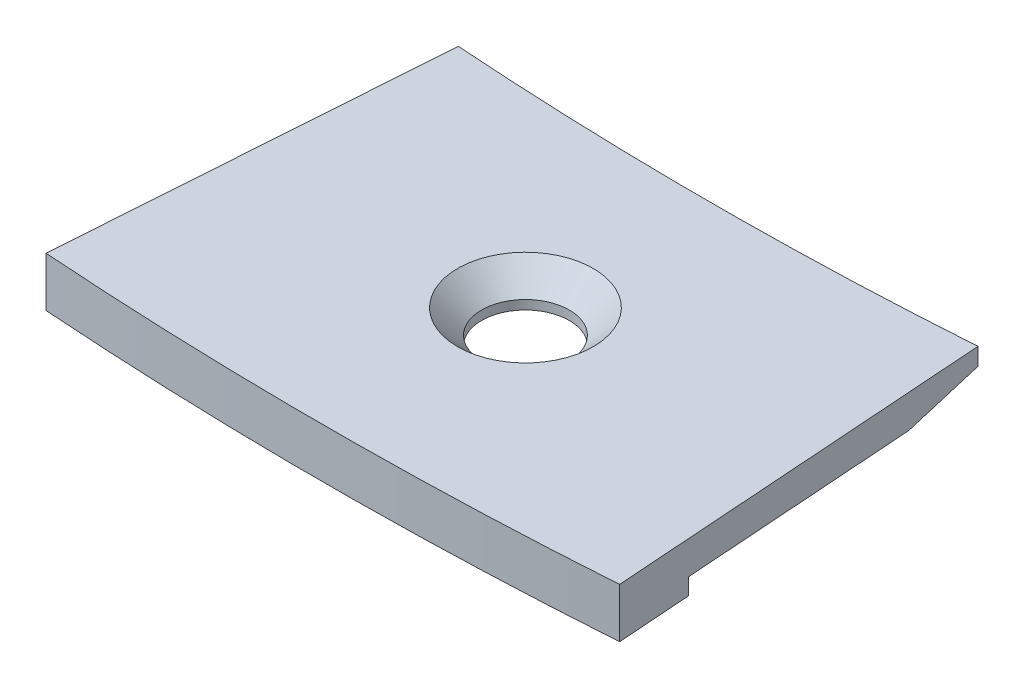
SolidWorks part; units mm, degrees
ref_plane "Front Plane" through (0, 0, 0) normal (0, 0, 1) x (1, 0, 0)
ref_plane "Top Plane" through (0, 0, 0) normal (0, 1, 0) x (1, 0, 0)
ref_plane "Right Plane" through (0, 0, 0) normal (1, 0, 0) x (0, 0, -1)
sketch "BASE" plane through (0, 0, 0) normal (0, 1, 0) x (1, 0, 0)
  line L0 (0, 0) -> (0, -243.5) construction
  line L1 (15.9742, -228.4422) -> (16.9857, -242.9068)
  line L2 (-15.9742, -228.4422) -> (-16.9857, -242.9068)
  line L3 (0, 0) -> (15.9742, -228.4422) construction
  line L4 (0, 0) -> (-15.9742, -228.4422) construction
  line L5 (0, -229) -> (0, -243.5) construction
  line L7 (-10, -226.25) -> (10, -226.25) construction
  line L8 (-10, -226.25) -> (-10, -246.25) construction
  line L9 (-10, -246.25) -> (10, -246.25) construction
  line L10 (10, -226.25) -> (10, -246.25) construction
  line L11 (-10, -226.25) -> (10, -246.25) construction
  line L12 (-10, -246.25) -> (10, -226.25) construction
  arc A0 (-16.9857, -242.9068) -> (16.9857, -242.9068) centre (0, 0) ccw
  arc A1 (-15.9742, -228.4422) -> (15.9742, -228.4422) centre (0, 0) ccw
  circle A2 centre (0, -236.25) radius 2.65
  dimension "D1" = 487
  dimension "D2" = 14.5
  dimension "D6" = 5.3
  dimension "D3" = 4
  dimension "D4" = 4
  dimension "D5" = 20
sketch "Sketch2" plane through (0, 0, 0) normal (0, 1, 0) x (1, 0, 0)
  line L1 (-15.9742, -228.4422) -> (-16.9857, -242.9068) construction
  line L3 (15.9742, -228.4422) -> (16.9857, -242.9068) construction
  line L4 (0, 0) -> (-17.3345, -247.8947) construction
  line L5 (0, 0) -> (17.3345, -247.8947) construction
  line L6 (-15.9847, -228.5918) -> (-17.3345, -247.8947)
  line L7 (15.9847, -228.5918) -> (17.3345, -247.8947)
  arc A0 (15.9847, -228.5918) -> (-15.9847, -228.5918) centre (0, 0) cw
  arc A1 (-15.9742, -228.4422) -> (15.9742, -228.4422) centre (0, 0) ccw construction
  arc A2 (17.3345, -247.8947) -> (-17.3345, -247.8947) centre (0, 0) cw
  arc A3 (-16.9857, -242.9068) -> (16.9857, -242.9068) centre (0, 0) ccw construction
  circle A4 centre (0, -236.25) radius 2.65
  dimension "D1" = 0.15
  dimension "D2" = 5
  dimension "D3" = 5.3
extrude "Boss-Extrude1" add sketch "Sketch2" along normal blind 2
sketch "Sketch3" plane through (0, 0, 0) normal (0, 1, 0) x (1, 0, 0)
  line L0 (0, 0) -> (15.9742, -228.4422) construction
  line L1 (0, 0) -> (-15.9742, -228.4422) construction
  line L2 (-15.7057, -224.6015) -> (-15.9847, -228.5918)
  line L3 (15.7057, -224.6015) -> (15.9847, -228.5918)
  arc A0 (15.9847, -228.5918) -> (-15.9847, -228.5918) centre (0, 0) cw
  arc A1 (15.7057, -224.6015) -> (-15.7057, -224.6015) centre (0, 0) cw
  dimension "D1" = 4
extrude "Boss-Extrude2" add sketch "Sketch3" against normal blind 2 from surface at 2 starting at face at (0, 2, 238.5341)
chamfer "Chamfer1" distance 4.5 angle 12 1 edges at (0, 0, 225.15)
sketch "Sketch4" plane through (0, 0, 0) normal (0, -1, 0) x (1, 0, 0)
  line L0 (15.9742, 228.4422) -> (16.9857, 242.9068) construction
  line L1 (-16.0196, 229.0906) -> (-17.3345, 247.8947) construction
  line L2 (17.3345, 247.8947) -> (16.0196, 229.0906) construction
  line L3 (-17.3345, 247.8947) -> (-17.0206, 243.4056)
  line L4 (17.3345, 247.8947) -> (17.0206, 243.4056)
  arc A0 (-17.0206, 243.4056) -> (17.0206, 243.4056) centre (0, 0) cw
  arc A1 (-17.3345, 247.8947) -> (17.3345, 247.8947) centre (0, 0) cw
  arc A2 (16.9857, 242.9068) -> (-16.9857, 242.9068) centre (0, 0) ccw construction
  arc A3 (17.3345, 247.8947) -> (-17.3345, 247.8947) centre (0, 0) ccw construction
  point P13 (0, 0)
  dimension "D2" = 0.5
extrude "Boss-Extrude3" add sketch "Sketch4" along normal blind 1
sketch "Sketch18" plane through (0, 2, 0) normal (0, 1, 0) x (1, 0, 0)
  circle A0 centre (0, -236.25) radius 4.225
  dimension "D1" = 8.45
hole_wizard "CSK for M3.5 Flat Head Machine Screw2" positions "Sketch19" profile "Sketch20" countersink size "M3.5" standard "ANSI Metric" end condition up to next
sketch "Sketch19" plane through (0, 2, 0) normal (0, 1, 0) x (1, 0, 0)
  point P0 (0, -236.25)
sketch "Sketch20" plane through (0, 2, 236.25) normal (1, 0, 0) x (0, 0, 1)
  line L0 (0, 0) -> (0, 3)
  line L1 (0, 3) -> (1.85, 3)
  line L2 (1.85, 3) -> (1.85, 2.25)
  line L3 (1.85, 2.25) -> (4.1, 0)
  line L5 (4.1, 0) -> (0, 0)
  line L6 (-1.85, 2.25) -> (-4.1, 0) construction
  line L11 (0, -6.35) -> (0, 107.95) construction
  dimension "Thru Hole Dia." = 3.7
  dimension "Thru Hole Depth" = 3
  dimension "Near C'Sink Dia." = 8.2
  dimension "Near C'Sink Angle" = 90
